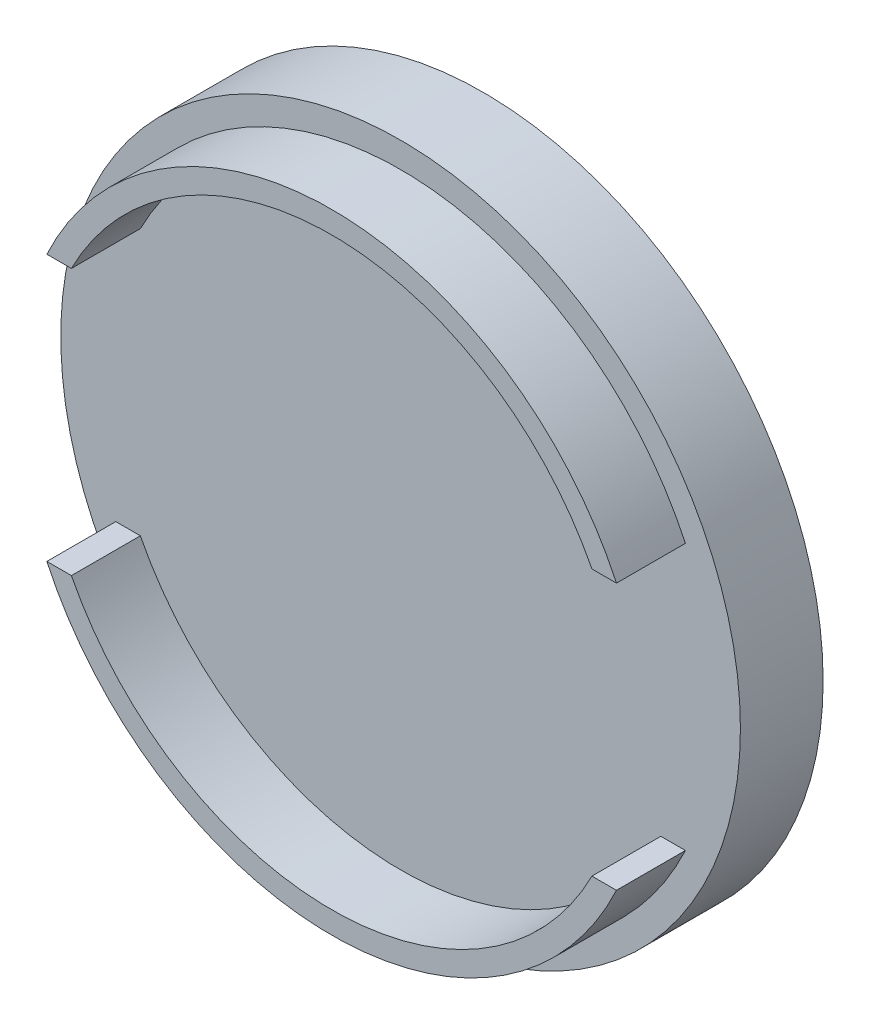
SolidWorks part; units mm, degrees
ref_plane "Front Plane" through (0, 0, 0) normal (0, 0, 1) x (1, 0, 0)
ref_plane "Top Plane" through (0, 0, 0) normal (0, 1, 0) x (1, 0, 0)
ref_plane "Right Plane" through (0, 0, 0) normal (1, 0, 0) x (0, 0, -1)
sketch "Sketch1" plane through (0, 0, 0) normal (0, 0, 1) x (1, 0, 0)
  circle A0 centre (0, 0) radius 24.65
extrude "Boss-Extrude1" add sketch "Sketch1" along normal blind 6
sketch "Sketch2" plane through (0, 0, 6) normal (0, 0, 1) x (1, 0, 0)
  circle A0 centre (0, 0) radius 22.8
  circle A1 centre (0, 0) radius 21.2
extrude "Boss-Extrude2" add sketch "Sketch2" along normal blind 5
sketch "Sketch3" plane through (0, 0, 11) normal (0, 0, 1) x (1, 0, 0)
  line L0 (-20.6585, 9.6472) -> (-18.8778, 9.6472)
  line L6 (20.6585, -9.6472) -> (18.8778, -9.6472)
  line L8 (18.8778, 9.6472) -> (20.6585, 9.6472)
  line L9 (-18.8778, -9.6472) -> (-20.6585, -9.6472)
  circle A0 centre (0, 0) radius 22.8 construction
  arc A1 (-20.6585, 9.6472) -> (-20.6585, -9.6472) centre (0, 0) ccw
  circle A2 centre (0, 0) radius 21.2 construction
  arc A3 (-18.8778, 9.6472) -> (-18.8778, -9.6472) centre (0, 0) ccw
  arc A4 (20.6585, -9.6472) -> (20.6585, 9.6472) centre (0, 0) ccw
  arc A5 (18.8778, -9.6472) -> (18.8778, 9.6472) centre (0, 0) ccw
extrude "Cut-Extrude1" cut sketch "Sketch3" against normal blind 5
